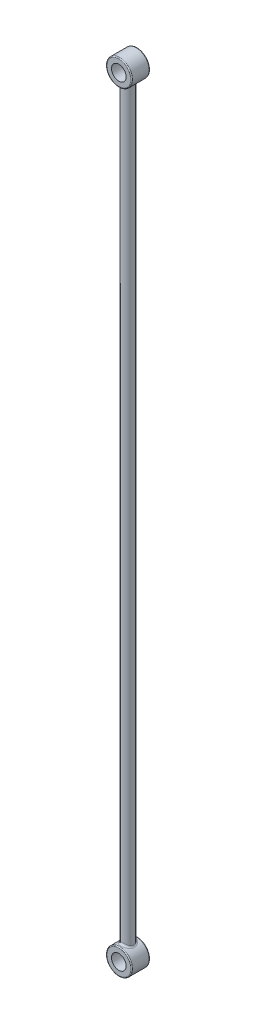
SolidWorks part; units mm, degrees
ref_plane "Front Plane" through (0, 0, 0) normal (0, 0, 1) x (1, 0, 0)
ref_plane "Top Plane" through (0, 0, 0) normal (0, 1, 0) x (1, 0, 0)
ref_plane "Right Plane" through (0, 0, 0) normal (1, 0, 0) x (0, 0, -1)
sketch "Sketch1" plane through (0, 0, 0) normal (0, 1, 0) x (1, 0, 0)
  circle A0 centre (0, 0) radius 1.5
  dimension "D1" = 3
extrude "Boss-Extrude1" add sketch "Sketch1" along normal mid plane 204
sketch "Sketch2" plane through (0, 0, 0) normal (0, 0, 1) x (1, 0, 0)
  circle A0 centre (0, 105) radius 3.5
  circle A1 centre (0, -105) radius 3.5
  circle A2 centre (0, 105) radius 2
  circle A3 centre (0, -105) radius 2
  dimension "D1" = 7
  dimension "D2" = 105
  dimension "D3" = 7
  dimension "D5" = 4
  dimension "D6" = 4
  dimension "D4" = 105
extrude "Boss-Extrude2" add sketch "Sketch2" along normal mid plane 5
fillet "Fillet3" radius 0.25 4 edges at (3.5, 105, -2.5) (3.5, 105, 2.5) (3.5, -105, -2.5) (3.5, -105, 2.5)
fillet "Fillet4" radius 0.5 2 edges at (0.1998, 101.5057, 1.4866) (-0.1998, -101.5057, 1.4866)
